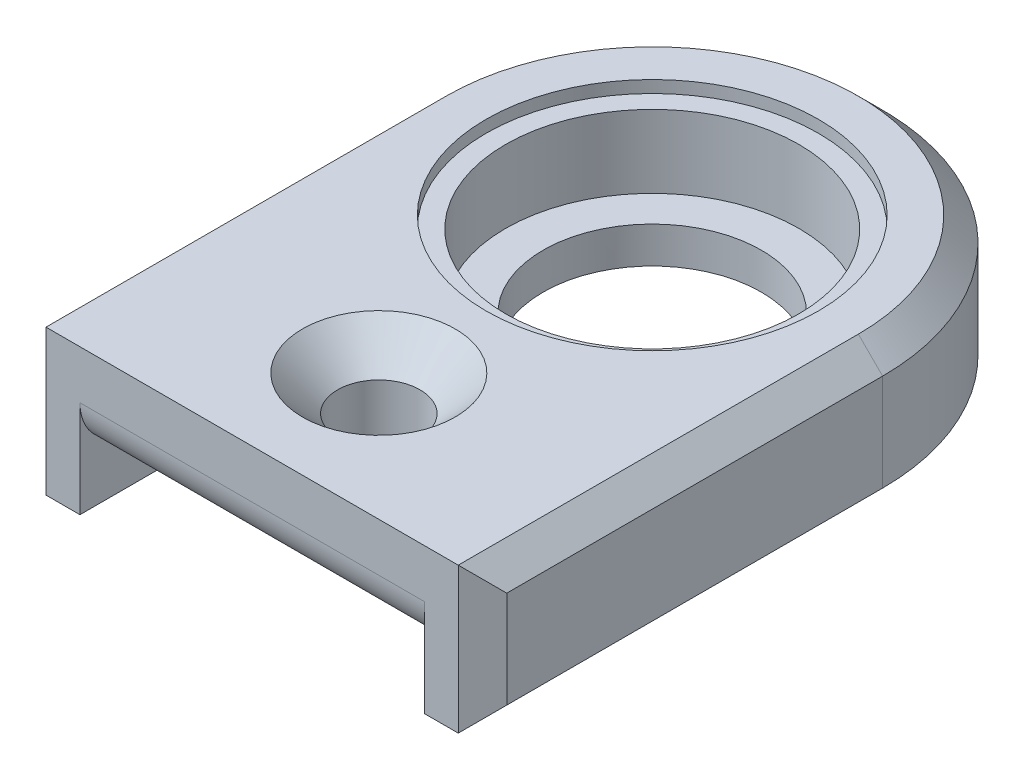
SolidWorks part; units mm, degrees
ref_plane "Front" through (0, 0, 0) normal (0, 0, 1) x (1, 0, 0)
ref_plane "Top" through (0, 0, 0) normal (0, 1, 0) x (1, 0, 0)
ref_plane "Right" through (0, 0, 0) normal (1, 0, 0) x (0, 0, -1)
sketch "Sketch2" plane through (0, 0, 0) normal (0, 1, 0) x (1, 0, 0)
  line L0 (-9.5, -16.5) -> (-9.5, 0)
  line L1 (9.5, 0) -> (9.5, -16.5)
  line L2 (9.5, -16.5) -> (-9.5, -16.5)
  line L3 (0, 0) -> (9.5, 0) construction
  arc A0 (-9.5, 0) -> (9.5, 0) centre (0, 0) cw
  dimension "D1" = 9.5
  dimension "D2" = 16.5
extrude "Boss-Extrude1" add sketch "Sketch2" along normal blind 6
sketch "Sketch1" plane through (0, 0, 0) normal (0, 1, 0) x (1, 0, 0)
  line L0 (-9.5, -16.5) -> (9.5, -16.5) construction
  line L6 (-7.1, 0) -> (-7.1, -16.5)
  line L7 (-7.1, -16.5) -> (7.1, -16.5)
  line L8 (7.1, -16.5) -> (7.1, 0)
  arc A2 (7.1, 0) -> (-7.1, 0) centre (0, 0) ccw
  dimension "D2" = 7.1
extrude "Cut-Extrude1" cut sketch "Sketch1" along normal blind 2
sketch "Sketch3" plane through (0, 6, 0) normal (0, 1, 0) x (1, 0, 0)
  circle A0 centre (0, 0) radius 6.05
  dimension "D1" = 12.1
extrude "Cut-Extrude2" cut sketch "Sketch3" against normal blind 3.5
sketch "Sketch4" plane through (0, 6, 0) normal (0, 1, 0) x (1, 0, 0)
  circle A0 centre (0, 0) radius 6.85
  dimension "D1" = 13.7
extrude "Cut-Extrude3" cut sketch "Sketch4" against normal blind 0.5
sketch "Sketch5" plane through (0, 2.5, 0) normal (0, 1, 0) x (1, 0, 0)
  circle A0 centre (0, 0) radius 4.5
  dimension "D1" = 9
extrude "Cut-Extrude4" cut sketch "Sketch5" against normal up to next
fillet "Fillet1" radius 2 1 edges at (0, 2, 16.5)
sketch "Sketch6" plane through (0, 2, 0) normal (0, -1, 0) x (1, 0, 0)
  circle A0 centre (0, 0) radius 5
  circle A1 centre (0, 0) radius 4.5 construction
  circle A3 centre (0, 0) radius 4.5
  dimension "D1" = 10
extrude "Boss-Extrude2" add sketch "Sketch6" along normal blind 1
hole_wizard "CSK for M3 Countersunk Flat Head Screw1" positions "Sketch8" profile "Sketch7" countersink size "M3" standard "ISO" end condition up to next
sketch "Sketch8" plane through (0, 6, 0) normal (0, 1, 0) x (1, 0, 0)
  line L0 (0, -6.05) -> (0, -16.5) construction
  line L1 (-9.5, -16.5) -> (9.5, -16.5) construction
  circle A0 centre (0, 0) radius 6.05 construction
  point P0 (0, -11.275)
sketch "Sketch7" plane through (0, 6, 11.275) normal (1, 0, 0) x (0, 0, 1)
  line L0 (0, 0) -> (0, 4)
  line L1 (0, 4) -> (1.7, 4)
  line L2 (1.7, 4) -> (1.7, 1.45)
  line L3 (1.7, 1.45) -> (3.15, 0)
  line L5 (3.15, 0) -> (0, 0)
  line L6 (-1.7, 1.45) -> (-3.15, 0) construction
  line L11 (0, -6.35) -> (0, 107.95) construction
  dimension "Thru Hole Dia." = 3.4
  dimension "Thru Hole Depth" = 4
  dimension "Near C'Sink Dia." = 6.3
  dimension "Near C'Sink Angle" = 90
chamfer "Chamfer1" distance 1 angle 45 8 edges at (9.5, 3, 16.5) (9.5, 0, 8.25) (9.5, 6, 8.25) (0, 0, -9.5) (0, 6, -9.5) (-9.5, 0, 8.25) (-9.5, 3, 16.5) (-9.5, 6, 8.25)
sketch "Sketch11" [suppressed] plane through (0, 0, 0) normal (1, 0, 0) x (0, 0, -1)
  line L0 (0, 0) -> (0, 9.1078) construction
  line L1 (0, 6) -> (-6.45, 6)
  line L2 (6.85, 6) -> (-6.85, 6) construction
  line L3 (-6.45, 6) -> (-6.45, 5.6)
  line L4 (-6.45, 5.6) -> (-6.05, 5.6)
  line L5 (-5.45, 5.8) -> (-5.45, 2.6)
  line L6 (-5.45, 2.6) -> (-5.05, 2.6)
  line L7 (-5.05, 2.6) -> (-5.05, 5.8)
  line L8 (-5.05, 5.8) -> (-4.65, 5.8)
  line L9 (0, 5.8) -> (0, 6)
  line L10 (-6.85, 6) -> (-6.85, 5.5) construction
  line L11 (-6.05, 5.6) -> (-6.05, 5.8)
  line L12 (-6.05, 5.8) -> (-5.45, 5.8)
  line L13 (-6.85, 5.5) -> (-6.05, 5.5) construction
  line L14 (-4.65, 5.8) -> (-4.65, 2.6)
  line L15 (-4.65, 2.6) -> (-4.25, 2.6)
  line L16 (-6.05, 5.5) -> (-6.05, 2.5) construction
  line L17 (-6.05, 2.5) -> (-4.5, 2.5) construction
  line L18 (-4.25, 2.6) -> (-4.25, 5.8)
  line L19 (-4.25, 5.8) -> (0, 5.8)
  dimension "D1" = 0.2
  dimension "D2" = 0.4
  dimension "D3" = 0.1
  dimension "D4" = 0.6
  dimension "D5" = 0.1
  dimension "D7" = 0.4
revolve "Revolve1" [suppressed] add sketch "Sketch11" angle 360 about L0
sketch "Sketch10" [suppressed] plane through (0, 6, 0) normal (0, 1, 0) x (1, 0, 0)
  circle A0 centre (0, -11.275) radius 3.15 construction
  circle A1 centre (0, -11.275) radius 3.15
  circle A2 centre (0, -11.275) radius 0.5
  dimension "D1" = 1
extrude "Boss-Extrude3" [suppressed] add sketch "Sketch10" against normal up to surface (4 mm away)
